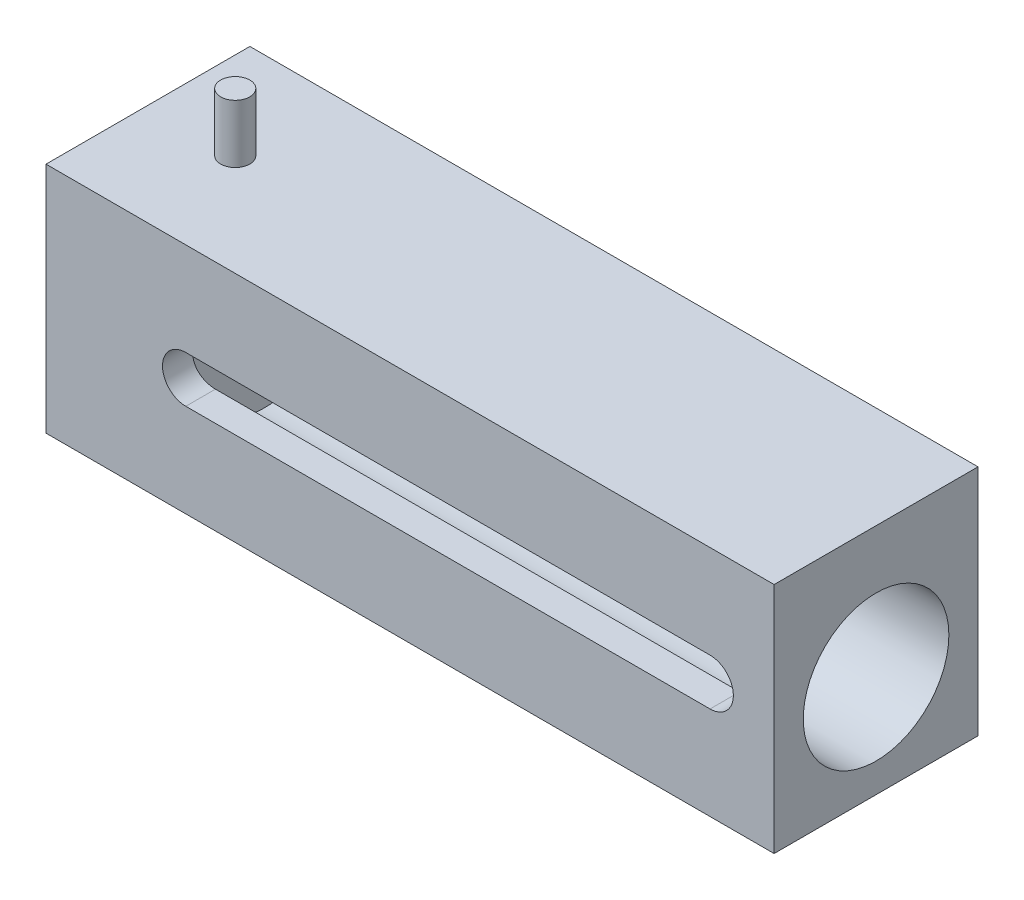
SolidWorks part; units mm, degrees
material "AISI 1020"
ref_plane "Front Plane" through (0, 0, 0) normal (0, 0, 1) x (1, 0, 0)
ref_plane "Top Plane" through (0, 0, 0) normal (0, 1, 0) x (1, 0, 0)
ref_plane "Right Plane" through (0, 0, 0) normal (1, 0, 0) x (0, 0, -1)
sketch "Sketch1" plane through (0, 0, 0) normal (0, 1, 0) x (1, 0, 0)
  line L1 (-125, 35) -> (125, 35)
  line L2 (-125, 35) -> (-125, -35)
  line L3 (-125, -35) -> (125, -35)
  line L4 (125, 35) -> (125, -35)
  line L5 (-125, 35) -> (125, -35) construction
  line L6 (-125, -35) -> (125, 35) construction
  point P0 (0, 0)
  dimension "D1" = 250
  dimension "D2" = 70
extrude "Boss-Extrude1" add sketch "Sketch1" along normal blind 80
sketch "Sketch2" plane through (125, 0, 0) normal (1, 0, 0) x (0, 0, -1)
  line L0 (0, -4.5384) -> (0, 41.5044) construction
  line L1 (-42.6238, 35) -> (8.4336, 35) construction
  circle A0 centre (0, 35) radius 25
  dimension "D1" = 50
  dimension "D2" = 35
extrude "Cut-Extrude1" cut sketch "Sketch2" against normal offset from surface (210 mm away) 40 up to face at (-125, 40, 0)
sketch "Sketch3" plane through (0, 0, 35) normal (0, 0, 1) x (1, 0, 0)
  line L0 (103, 40) -> (-77, 40) construction
  line L1 (103, 32) -> (-77, 32)
  line L2 (103, 48) -> (-77, 48)
  line L3 (-125, 80) -> (-125, 0) construction
  line L4 (125, 80) -> (125, 0) construction
  arc A0 (103, 32) -> (103, 48) centre (103, 40) ccw
  arc A1 (-77, 48) -> (-77, 32) centre (-77, 40) ccw
  point P2 (13, 40)
  dimension "D3" = 8
  dimension "D1" = 40
  dimension "D2" = 30
extrude "Cut-Extrude2" cut sketch "Sketch3" against normal up to next
sketch "Sketch4" plane through (0, 80, 0) normal (0, 1, 0) x (1, 0, 0)
  circle A0 centre (-95.027, 0) radius 5
  dimension "D1" = 10
extrude "Boss-Extrude2" add sketch "Sketch4" along normal blind 20
